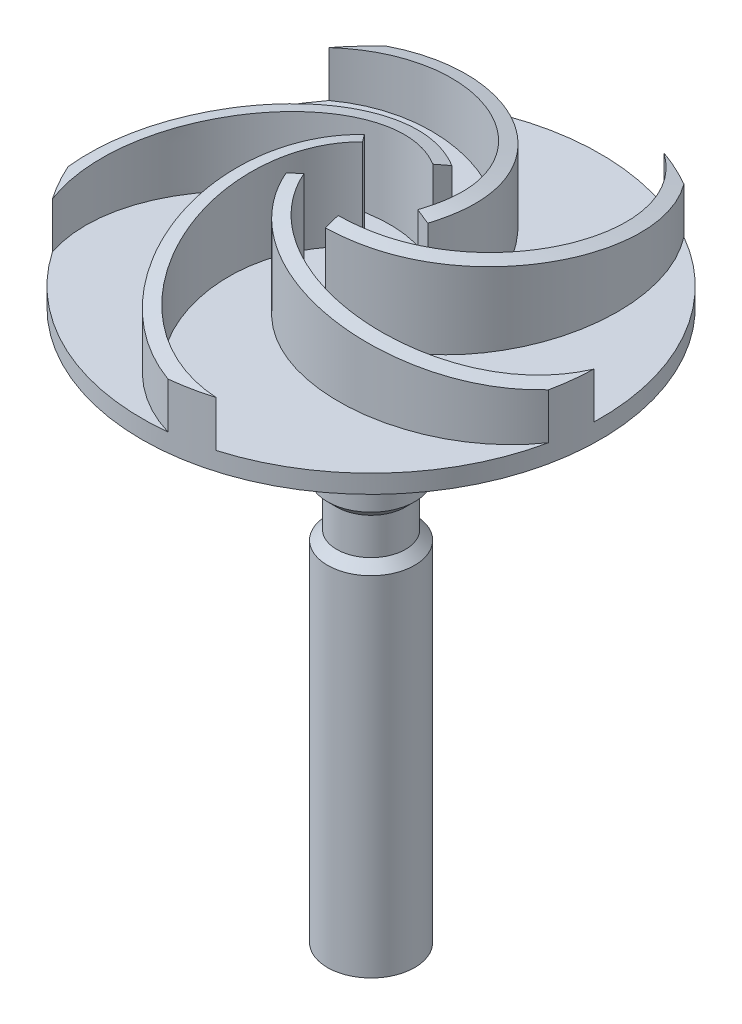
SolidWorks part; units mm, degrees
ref_plane "Front Plane" through (0, 0, 0) normal (0, 0, 1) x (1, 0, 0)
ref_plane "Top Plane" through (0, 0, 0) normal (0, 1, 0) x (1, 0, 0)
ref_plane "Right Plane" through (0, 0, 0) normal (1, 0, 0) x (0, 0, -1)
sketch "Sketch1" plane through (0, 0, 0) normal (0, 1, 0) x (1, 0, 0)
  circle A0 centre (0, 0) radius 25
  dimension "D1" = 50
extrude "Boss-Extrude1" add sketch "Sketch1" along normal blind 2
sketch "Sketch6" plane through (0, 2, 0) normal (0, 1, 0) x (1, 0, 0)
  line L0 (-5.7493, -3.5145) -> (-4.3579, -2.9543)
  circle A1 centre (0, 0) radius 6 construction
  circle A2 centre (0, 0) radius 25 construction
  arc A3 (24.9909, -0.6741) -> (24.4716, -5.1127) centre (0, 0) cw
  spline S0 degree 1 poles (25.0627, -0.4446) (-4.3579, -2.9543) knots 0 0 1 1 construction
  spline S1 degree 3 poles (25.7803, -0.6625) (21.6404, -14.2953) (0.0983, -16.0311) (-5.0536, -3.2344) knots 0 0 0 0 1 1 1 1 construction
  spline S2 degree 3 poles (25.0627, -0.4446) (24.9415, -0.8439) (24.6609, -1.6391) (23.9856, -3.1188) (22.9273, -4.8072) (21.3623, -6.5622) (18.9387, -8.5421) (15.3904, -10.3257) (10.688, -11.311) (5.9458, -11.1024) (2.2991, -9.9186) (-0.2437, -8.3638) (-1.92, -6.8935) (-3.0916, -5.407) (-3.8701, -4.0639) (-4.2082, -3.326) (-4.3579, -2.9543) knots 0 0 0 0 0.03125 0.0625 0.125 0.1875 0.25 0.375 0.5 0.625 0.75 0.8125 0.875 0.9375 0.96875 1 1 1 1 only from (24.9909, -0.6741) to (-4.3579, -2.9543)
  spline S3 degree 1 poles (26.498, -0.8804) (-5.7493, -3.5145) knots 0 0 1 1 construction
  spline S4 degree 3 poles (26.498, -0.8804) (26.3639, -1.322) (26.054, -2.2007) (25.3054, -3.8411) (24.1316, -5.7133) (22.4022, -7.6519) (19.741, -9.8246) (15.8842, -11.7596) (10.8135, -12.821) (5.6878, -12.5982) (1.6922, -11.3067) (-1.1345, -9.5799) (-3.0133, -7.9327) (-4.3313, -6.2609) (-5.2048, -4.7532) (-5.5821, -3.9299) (-5.7493, -3.5145) knots 0 0 0 0 0.03125 0.0625 0.125 0.1875 0.25 0.375 0.5 0.625 0.75 0.8125 0.875 0.9375 0.96875 1 1 1 1 only from (24.4716, -5.1127) to (-5.7493, -3.5145)
  point P2 (-4.5906, -3.8635)
  point P3 (0.6155, -10.8178)
  point P5 (12.8473, -11.8485)
  circle M3 centre (0, 0) radius 25
  dimension "D1" = 12
  dimension "D4" = 0.6155
  dimension "D5" = 12.8473
  dimension "D6" = 24.4716
  dimension "D7" = 24.9909
  dimension "D8" = 25.7803
  dimension "D9" = 4.3579
  dimension "D10" = 5.0536
  dimension "D2" = 0.75
  dimension "D3" = 0.75
extrude "Boss-Extrude3" add sketch "Sketch6" along normal blind 11 contours S4 S2 L0 M3
pattern_circular "CirPattern2" count 5 over 360 about axis through (0, 0, 0) along (0, 1, 0) of "Boss-Extrude3"
sketch "Sketch7" plane through (0, 0, 0) normal (1, 0, 0) x (0, 0, -1)
  line L0 (25, 7) -> (25, 13)
  line L1 (25, 13) -> (1, 13)
  line L2 (21.694, 13) -> (-6.554, 13) construction
  line L3 (1, 13) -> (25, 7)
  line L4 (0, 0) -> (0, 5.0173) construction
  point P3 (1.1879, 13)
  dimension "D1" = 5
  dimension "D2" = 1
revolve "Cut-Revolve7" cut sketch "Sketch7" angle 360 about L4
sketch "Sketch8" plane through (0, 0, 0) normal (0, -1, 0) x (1, 0, 0)
  circle A0 centre (0, 0) radius 4.75
  dimension "D1" = 9.5
extrude "Boss-Extrude4" add sketch "Sketch8" along normal blind 60
sketch "Sketch9" plane through (0, 0, 0) normal (0, 0, 1) x (1, 0, 0)
  line L0 (-4.75, -16) -> (-3.75, -17)
  line L1 (-4.75, 0) -> (-4.75, -60) construction
  line L2 (-3.75, -17) -> (-3.75, -21)
  line L3 (-3.75, -21) -> (-4.75, -22)
  line L4 (-4.75, -22) -> (-4.75, -16)
  line L5 (0, 0) -> (0, -60) construction
  line L6 (-4.75, -60) -> (4.75, -60) construction
  dimension "D1" = 22
  dimension "D2" = 6
  dimension "D3" = 1
  dimension "D4" = 45
revolve "Cut-Revolve8" cut sketch "Sketch9" angle 360 about L5
